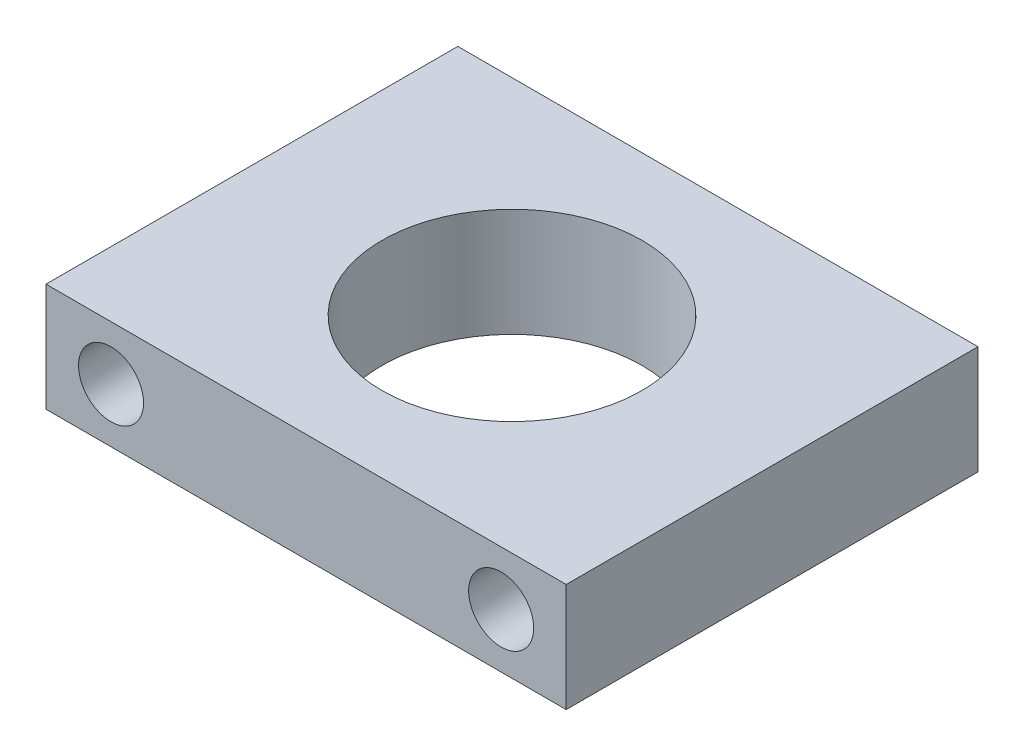
SolidWorks part; units mm, degrees
ref_plane "前视基准面" through (0, 0, 0) normal (0, 0, 1) x (1, 0, 0)
ref_plane "上视基准面" through (0, 0, 0) normal (0, 1, 0) x (1, 0, 0)
ref_plane "右视基准面" through (0, 0, 0) normal (1, 0, 0) x (0, 0, -1)
sketch "草图1" plane through (0, 0, 0) normal (0, 1, 0) x (1, 0, 0)
  line L1 (-12, 9.5) -> (12, 9.5)
  line L2 (-12, 9.5) -> (-12, -9.5)
  line L3 (-12, -9.5) -> (12, -9.5)
  line L4 (12, 9.5) -> (12, -9.5)
  line L5 (-12, 9.5) -> (12, -9.5) construction
  line L6 (-12, -9.5) -> (12, 9.5) construction
  point P0 (0, 0)
  dimension "D1" = 24
  dimension "D2" = 19
extrude "凸台-拉伸1" add sketch "草图1" along normal blind 5
sketch "草图2" plane through (0, 5, 0) normal (0, 1, 0) x (1, 0, 0)
  circle A0 centre (0, 0) radius 6
  dimension "D1" = 12
extrude "切除-拉伸1" cut sketch "草图2" against normal up to next
sketch "草图3" plane through (0, 0, 9.5) normal (0, 0, 1) x (1, 0, 0)
  line L0 (0, 0) -> (0, 5) construction
  line L1 (-12, 5) -> (12, 5) construction
  line L2 (-9, 2.5) -> (9, 2.5) construction
  circle A0 centre (-9, 2.5) radius 1.5
  circle A1 centre (9, 2.5) radius 1.5
  point P8 (0, 2.5)
  dimension "D2" = 3
  dimension "D1" = 18
extrude "切除-拉伸2" cut sketch "草图3" against normal up to next
